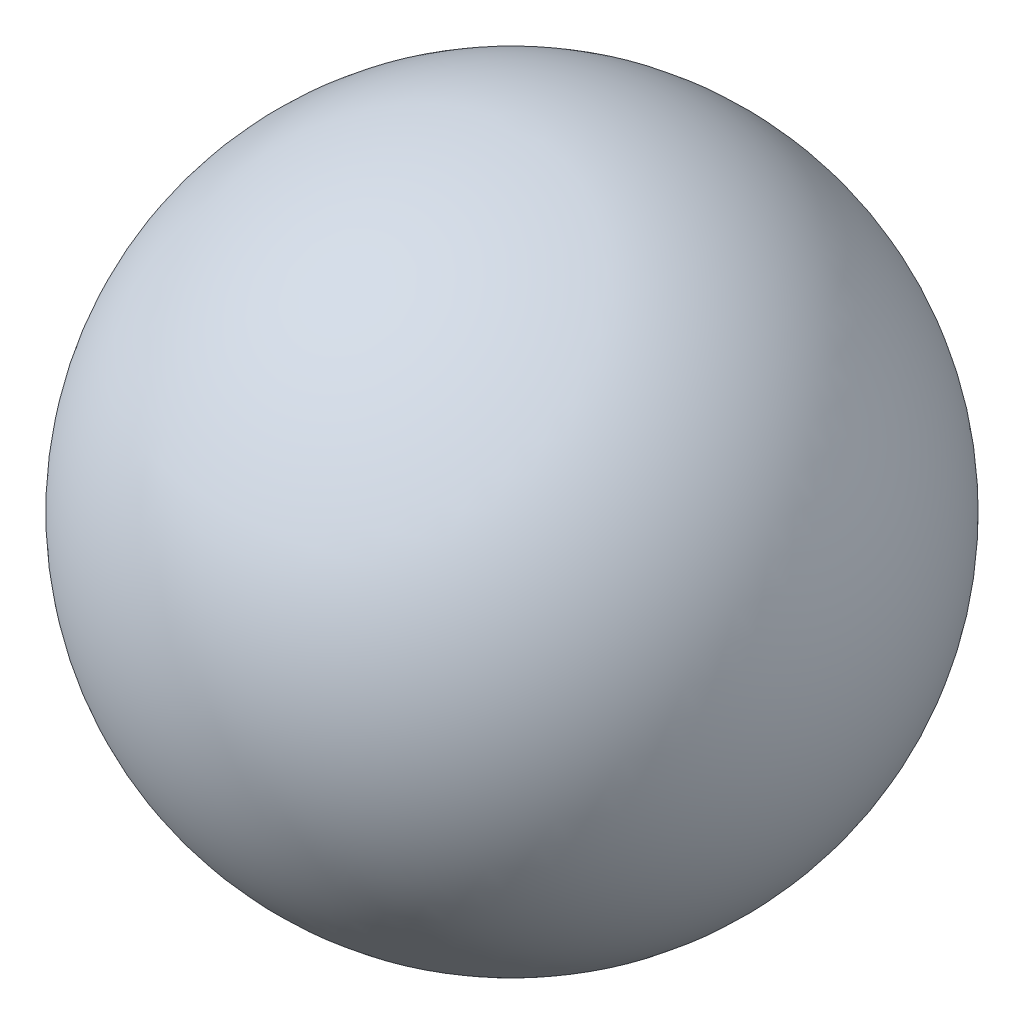
SolidWorks part; units mm, degrees
material "Copper"
ref_plane "Front Plane" through (0, 0, 0) normal (0, 0, 1) x (1, 0, 0)
ref_plane "Top Plane" through (0, 0, 0) normal (0, 1, 0) x (1, 0, 0)
ref_plane "Right Plane" through (0, 0, 0) normal (1, 0, 0) x (0, 0, -1)
sketch "Sketch1" plane through (0, 0, 0) normal (0, 0, 1) x (1, 0, 0)
  line L0 (0, -1000) -> (0, 49000) construction
  line L1 (0, -12.7) -> (0, 12.7)
  arc A0 (0, 12.7) -> (0, -12.7) centre (0, 0) ccw
  dimension "D1" = 25.4
revolve "Main Revolve" add sketch "Sketch1" angle 360 about L0
